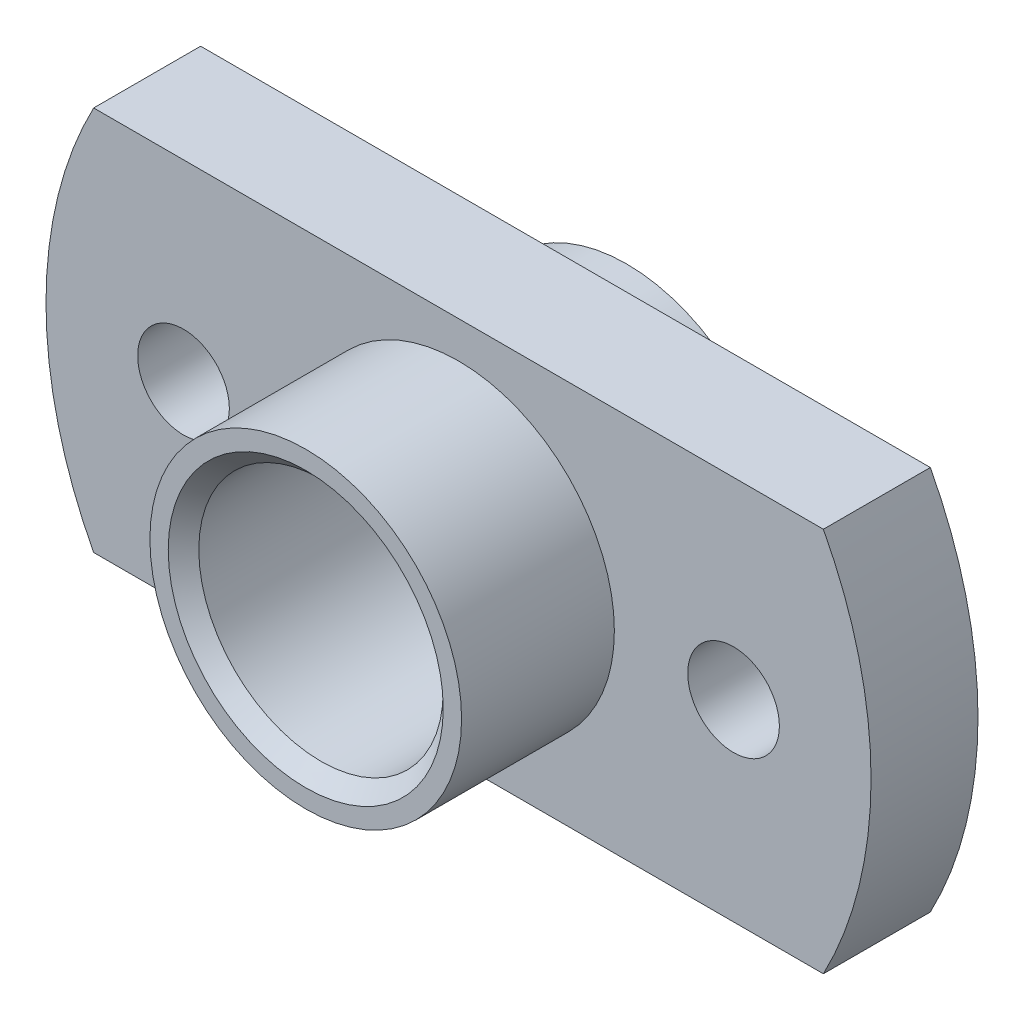
SolidWorks part; units mm, degrees
material "Mosaz"
ref_plane "Přední rovina" through (0, 0, 0) normal (0, 0, 1) x (1, 0, 0)
ref_plane "Horní rovina" through (0, 0, 0) normal (0, 1, 0) x (1, 0, 0)
ref_plane "Pravá rovina" through (0, 0, 0) normal (1, 0, 0) x (0, 0, -1)
sketch "Skica1" plane through (0, 0, 0) normal (0, 0, 1) x (1, 0, 0)
  line L0 (-11.9398, 6.3) -> (11.9398, 6.3)
  line L1 (-11.9398, -6.3) -> (11.9398, -6.3)
  line L2 (-13.5, 0) -> (13.5, 0) construction
  line L3 (0, 6.3) -> (0, -6.3) construction
  arc A0 (-11.9398, 6.3) -> (-11.9398, -6.3) centre (0, 0) ccw
  arc A1 (11.9398, -6.3) -> (11.9398, 6.3) centre (0, 0) ccw
  circle A2 centre (-9, 0) radius 1.5
  circle A3 centre (9, 0) radius 1.5
  point P14 (0, 0)
  dimension "D1" = 27
  dimension "D3" = 3
  dimension "D4" = 3
  dimension "D2" = 12.6
  dimension "D5" = 18
extrude "Přidat vysunutím1" add sketch "Skica1" along normal blind 3.5
sketch "Skica2" plane through (0, 0, 3.5) normal (0, 0, 1) x (1, 0, 0)
  circle A0 centre (0, 0) radius 5.1
  dimension "D1" = 10.2
extrude "Přidat vysunutím2" add sketch "Skica2" along normal blind 5 and the other way blind 5.5
sketch "Skica3" plane through (0, 0, 8.5) normal (0, 0, 1) x (1, 0, 0)
  circle A0 centre (0, 0) radius 4
  dimension "D1" = 8
extrude "Odebrat vysunutím1" cut sketch "Skica3" against normal up to surface (10.5 mm away) up to face at (5.1, 0, -2)
chamfer "Zkosení1" distance 0.5 angle 45 2 edges at (4, 0, -2) (4, 0, 8.5)
